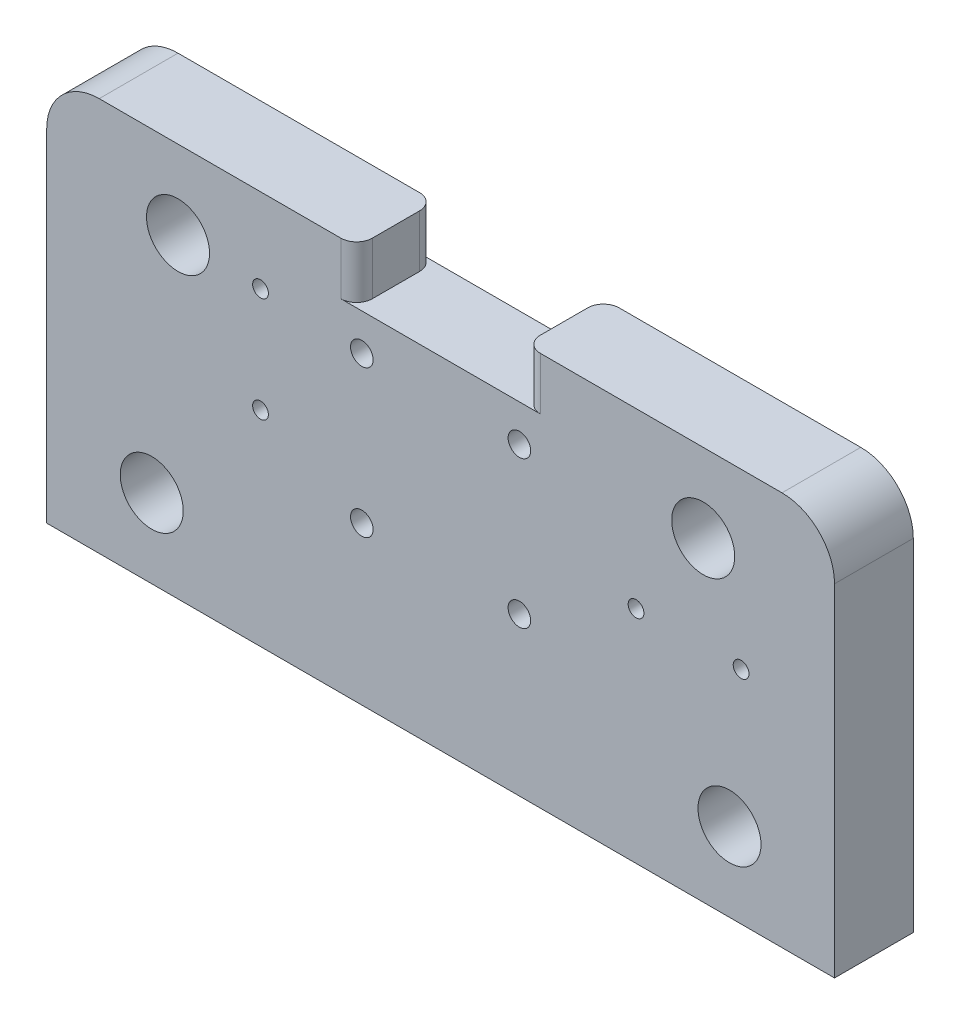
SolidWorks part; units mm, degrees
material "三聚氰胺甲醛树脂"
ref_plane "前视基准面" through (0, 0, 0) normal (0, 0, 1) x (1, 0, 0)
ref_plane "上视基准面" through (0, 0, 0) normal (0, 1, 0) x (1, 0, 0)
ref_plane "右视基准面" through (0, 0, 0) normal (1, 0, 0) x (0, 0, -1)
sketch "草图1" plane through (0, 0, 0) normal (0, 0, 1) x (1, 0, 0)
  line L0 (16, 37.5) -> (65, 37.5)
  line L1 (-65, 37.5) -> (-16, 37.5)
  line L2 (-75, 27.5) -> (-75, -37.5)
  line L3 (-75, -37.5) -> (75, -37.5)
  line L4 (75, 27.5) -> (75, -37.5)
  line L5 (-75, 37.5) -> (75, -37.5) construction
  line L6 (-75, -37.5) -> (75, 37.5) construction
  line L8 (-16, 37.5) -> (-16, 27.5)
  line L9 (-16, 27.5) -> (16, 27.5)
  line L10 (16, 37.5) -> (16, 27.5)
  arc A0 (-75, 27.5) -> (-65, 37.5) centre (-65, 27.5) cw
  arc A1 (75, 27.5) -> (65, 37.5) centre (65, 27.5) ccw
  circle A2 centre (-15, 20.5) radius 2.15
  circle A3 centre (15, 20.5) radius 2.15
  circle A4 centre (-15, -7.5) radius 2.15
  circle A5 centre (15, -7.5) radius 2.15
  point P0 (0, 0)
  point P20 (0, 27.5)
  dimension "D6" = 10
  dimension "D7" = 10
  dimension "D8" = 4.3
  dimension "D9" = 4.3
  dimension "D11" = 15
  dimension "D13" = 0
  dimension "D14" = 28
  dimension "D18" = 4.3
  dimension "D19" = 4.3
  dimension "D1" = 75
  dimension "D2" = 150
  dimension "D3" = 10
  dimension "D4" = 32
  dimension "D5" = 59
  dimension "D10" = 30
  dimension "D12" = 7
  dimension "D15" = 28
  dimension "D16" = 30
  dimension "D17" = 0
extrude "凸台-拉伸1" add sketch "草图1" along normal blind 15 contours A2 | A3 | L1 L8 L9 L10 L0 A1 L4 L3 L2 A0 | A5 | A4
sketch "草图2" plane through (0, 0, 15) normal (0, 0, 1) x (1, 0, 0)
  line L0 (-16, 27.5) -> (16, 27.5) construction
  line L1 (-75, -37.5) -> (75, -37.5) construction
  line L2 (-65, 37.5) -> (-16, 37.5) construction
  circle A0 centre (-50, 22.5) radius 6
  circle A1 centre (50, 22.5) radius 6
  circle A2 centre (-55, -22.5) radius 6
  circle A3 centre (55, -22.5) radius 6
  point P10 (0, 27.5)
  dimension "D1" = 12
  dimension "D2" = 12
  dimension "D3" = 12
  dimension "D4" = 12
  dimension "D6" = 0
  dimension "D7" = 100
  dimension "D9" = 50
  dimension "D11" = 15
  dimension "D12" = 15
  dimension "D5" = 110
  dimension "D8" = 55
  dimension "D10" = 0
extrude "切除-拉伸1" cut sketch "草图2" against normal through all
fillet "圆角1" radius 3 4 edges at (16, 32.5, 0) (16, 32.5, 15) (-16, 32.5, 0) (-16, 32.5, 15)
sketch "草图3" plane through (0, 0, 15) normal (0, 0, 1) x (1, 0, 0)
  line L0 (-75, 27.5) -> (-75, -37.5) construction
  line L1 (-65, 37.5) -> (-19, 37.5) construction
  circle A0 centre (-34.29, 1.5) radius 1.5
  circle A1 centre (-34.29, 21.5) radius 1.5
  point P8 (-28.1538, 21.5)
  dimension "D1" = 40.71
  dimension "D2" = 36
  dimension "D3" = 20
  dimension "D4" = 3
  dimension "D5" = 3
  dimension "D6" = 0
extrude "切除-拉伸2" cut sketch "草图3" against normal through all
sketch "草图4" plane through (0, 0, 15) normal (0, 0, 1) x (1, 0, 0)
  line L0 (75, 27.5) -> (75, -37.5) construction
  line L1 (19, 37.5) -> (65, 37.5) construction
  circle A0 centre (57.21, 4.5) radius 1.5
  circle A1 centre (37.21, 4.5) radius 1.5
  point P8 (0, 0)
  dimension "D1" = 17.79
  dimension "D2" = 33
  dimension "D3" = 3
  dimension "D4" = 3
  dimension "D5" = 20
  dimension "D6" = 0
extrude "切除-拉伸3" cut sketch "草图4" against normal through all contours A0 | A1
